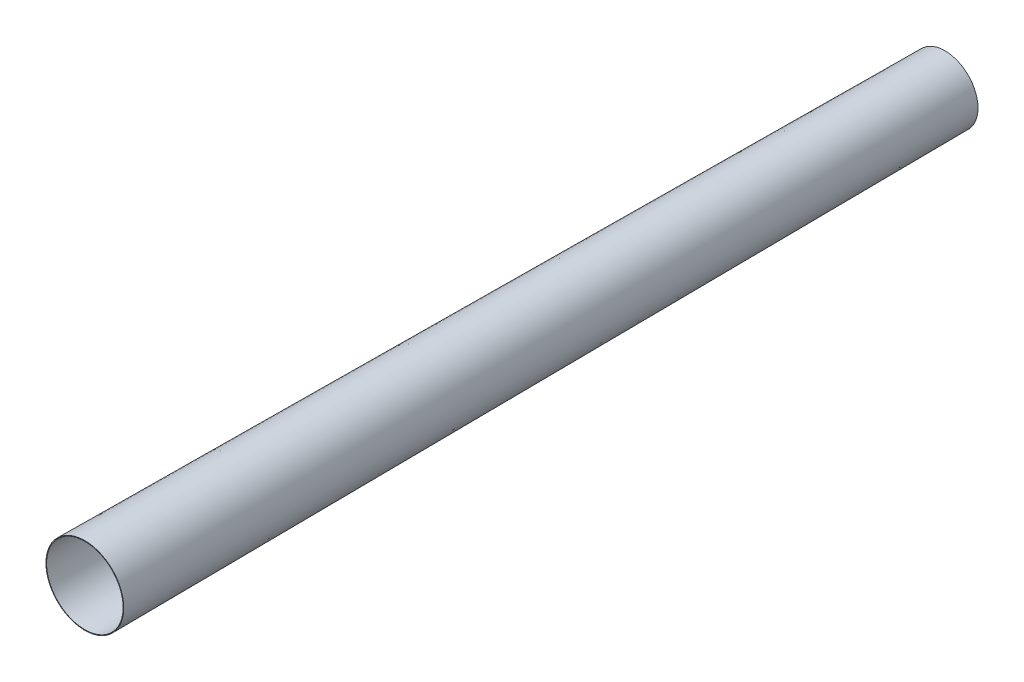
SolidWorks part; units mm, degrees
ref_plane "Front Plane" through (0, 0, 0) normal (0, 0, 1) x (1, 0, 0)
ref_plane "Top Plane" through (0, 0, 0) normal (0, 1, 0) x (1, 0, 0)
ref_plane "Right Plane" through (0, 0, 0) normal (1, 0, 0) x (0, 0, -1)
sketch "Sketch1" plane through (0, 0, 0) normal (0, 0, 1) x (1, 0, 0)
  circle A0 centre (0, 0) radius 26.4374
  circle A1 centre (0, 0) radius 26.9374
  dimension "D2" = 53.8748
  dimension "D1" = 0.5
ref_plane "Plane1" through (0, 0, 700.9946) normal (0, 0, 1) x (1, 0, 0)
sketch "Sketch2" plane through (0, 0, 700.9946) normal (0, 0, 1) x (1, 0, 0)
  circle A0 centre (0, 0) radius 31.7033
  circle A1 centre (0, 0) radius 31.2033
  dimension "D2" = 63.4065
  dimension "D1" = 0.5
loft "Loft1" add section "Sketch1" section "Sketch2"
shell "Shell1" thickness 0.5
